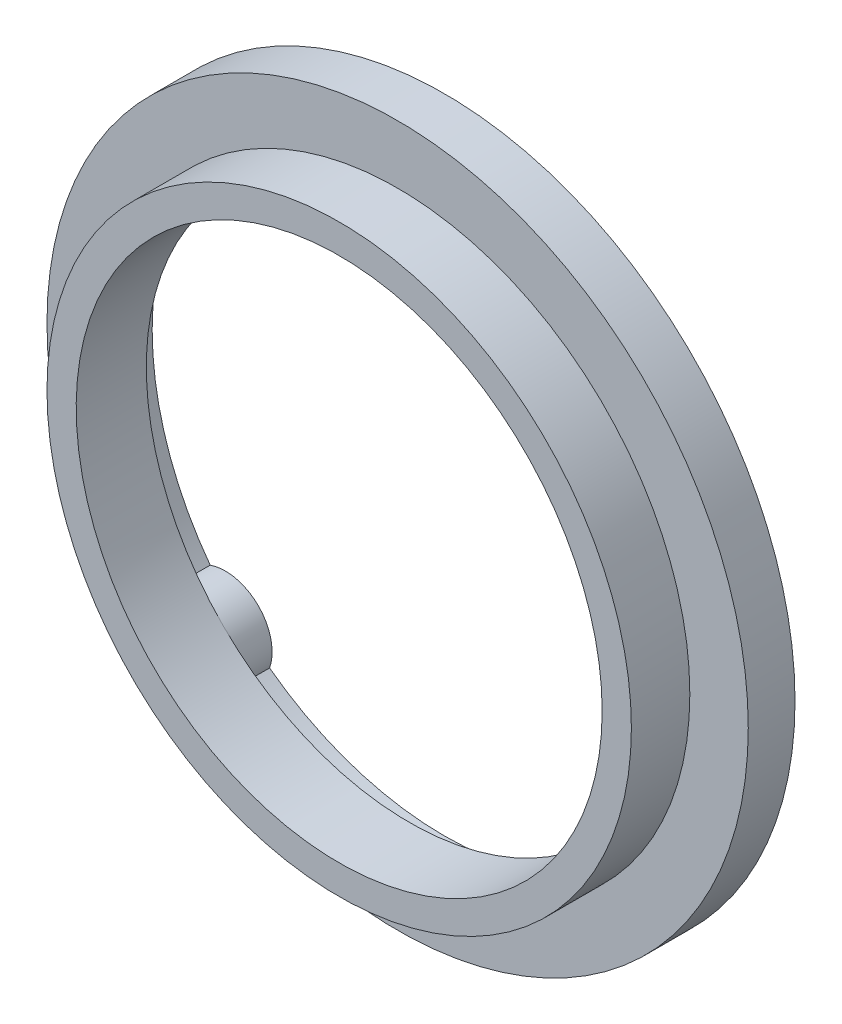
SolidWorks part; units mm, degrees
ref_plane "前视基准面" through (0, 0, 0) normal (0, 0, 1) x (1, 0, 0)
ref_plane "上视基准面" through (0, 0, 0) normal (0, 1, 0) x (1, 0, 0)
ref_plane "右视基准面" through (0, 0, 0) normal (1, 0, 0) x (0, 0, -1)
other "Configuration Table"
sketch "草图2" plane through (0, 0, 0) normal (0, 0, 1) x (1, 0, 0)
  arc A12 (-116.6066, -63.7835) -> (-86.6066, -93.7835) centre (-86.6066, -63.7835) ccw
  arc A13 (-86.6066, -93.7835) -> (-56.6066, -63.7835) centre (-86.6066, -63.7835) ccw
  arc A14 (-56.6066, -63.7835) -> (-86.6066, -33.7835) centre (-86.6066, -63.7835) ccw
  arc A15 (-86.6066, -33.7835) -> (-116.6066, -63.7835) centre (-86.6066, -63.7835) ccw
  arc A16 (-106.641, -48.8294) -> (-101.5608, -43.7492) centre (-105.345, -45.0452) ccw
  arc A17 (-106.641, -48.8294) -> (-106.641, -78.7376) centre (-86.6066, -63.7835) ccw
  arc A18 (-101.5608, -83.8179) -> (-106.641, -78.7376) centre (-105.345, -82.5219) ccw
  arc A19 (-101.5608, -83.8179) -> (-71.6525, -83.8179) centre (-86.6066, -63.7835) ccw
  arc A20 (-66.5723, -78.7376) -> (-71.6525, -83.8179) centre (-67.8683, -82.5219) ccw
  arc A21 (-66.5723, -78.7376) -> (-66.5723, -48.8294) centre (-86.6066, -63.7835) ccw
  arc A22 (-71.6525, -43.7492) -> (-66.5723, -48.8294) centre (-67.8683, -45.0452) ccw
  arc A23 (-71.6525, -43.7492) -> (-101.5608, -43.7492) centre (-86.6066, -63.7835) ccw
extrude "凸台-拉伸1" add sketch "草图2" along normal blind 3
sketch "草图3" plane through (0, 0, 3) normal (0, 0, 1) x (1, 0, 0)
  circle A0 centre (-86.6066, -63.7835) radius 22.5
  circle A1 centre (-86.6066, -63.7835) radius 30
extrude "凸台-拉伸2" add sketch "草图3" along normal blind 1
sketch "草图4" plane through (0, 0, 4) normal (0, 0, 1) x (1, 0, 0)
  circle A0 centre (-86.6066, -63.7835) radius 22.5
  circle A1 centre (-86.6066, -63.7835) radius 25
extrude "凸台-拉伸3" add sketch "草图4" along normal blind 5
